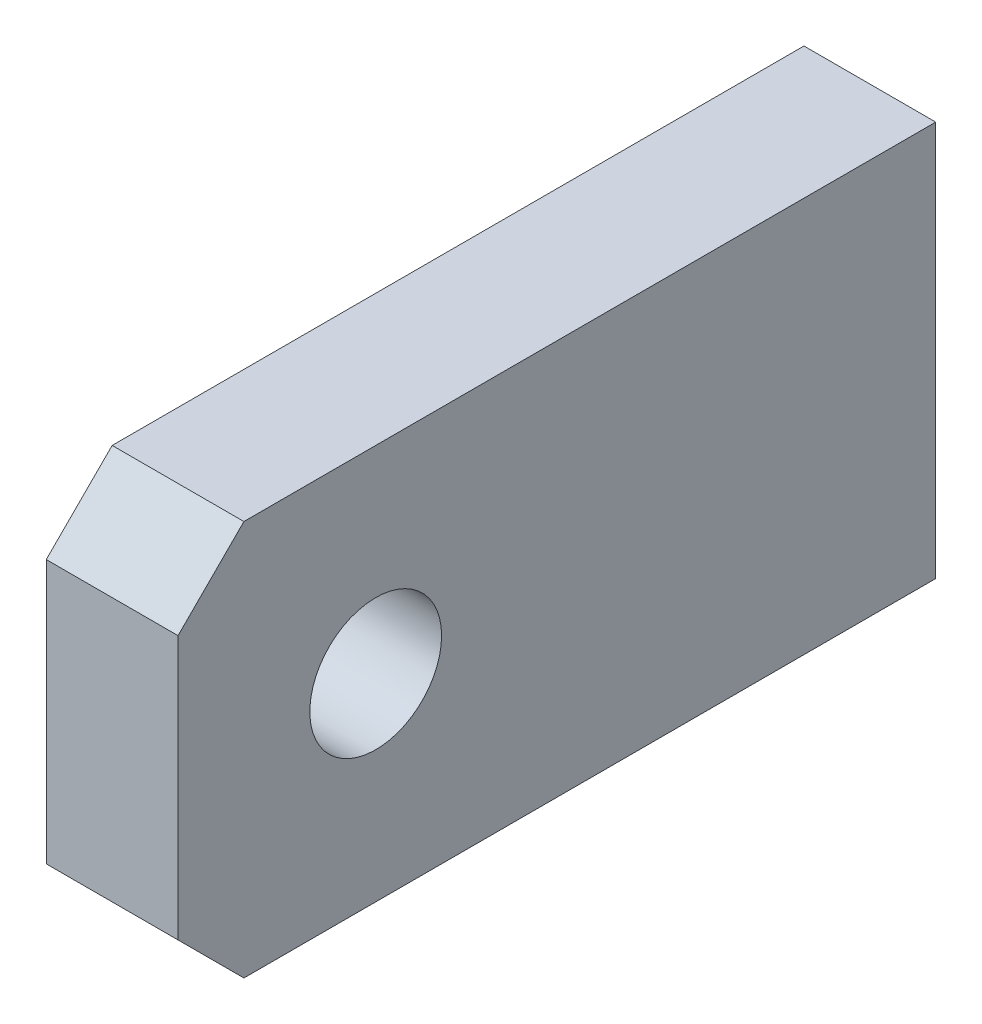
SolidWorks part; units mm, degrees
ref_plane "Front Plane" through (0, 0, 0) normal (0, 0, 1) x (1, 0, 0)
ref_plane "Top Plane" through (0, 0, 0) normal (0, 1, 0) x (1, 0, 0)
ref_plane "Right Plane" through (0, 0, 0) normal (1, 0, 0) x (0, 0, -1)
sketch "Sketch1" plane through (0, 0, 0) normal (1, 0, 0) x (0, 0, -1)
  line L1 (-11.5, -6) -> (11.5, -6)
  line L2 (-11.5, -6) -> (-11.5, 6)
  line L3 (-11.5, 6) -> (11.5, 6)
  line L4 (11.5, -6) -> (11.5, 6)
  line L5 (-11.5, -6) -> (11.5, 6) construction
  line L6 (-11.5, 6) -> (11.5, -6) construction
  point P0 (0, 0)
  dimension "D1" = 23
  dimension "D2" = 12
extrude "Boss-Extrude1" add sketch "Sketch1" along normal blind 4 contours L2 L3 L4 L1
sketch "Sketch2" plane through (0, 0, -11.5) normal (0, 0, -1) x (-1, 0, 0)
  line L1 (-4, 6) -> (0, 6) construction
  line L2 (-4, -6) -> (0, -6) construction
  circle A0 centre (-1.9644, -4) radius 1.5
  circle A1 centre (-1.9644, 4) radius 1.5
  dimension "D1" = 3
  dimension "D3" = 3
  dimension "D2" = 2
  dimension "D4" = 2
extrude "Cut-Extrude2" cut sketch "Sketch2" against normal blind 10
sketch "Sketch3" plane through (4, 0, 0) normal (1, 0, 0) x (0, 0, -1)
  line L0 (-11.5, 6) -> (11.5, 6) construction
  line L1 (11.5, -6) -> (11.5, 6) construction
  circle A0 centre (-5.5, 0) radius 2
  dimension "D1" = 4
  dimension "D2" = 6
  dimension "D3" = 17
extrude "Cut-Extrude3" cut sketch "Sketch3" against normal through all
chamfer "Chamfer1" distance 2 angle 45 2 edges at (2, -6, 11.5) (2, 6, 11.5)
